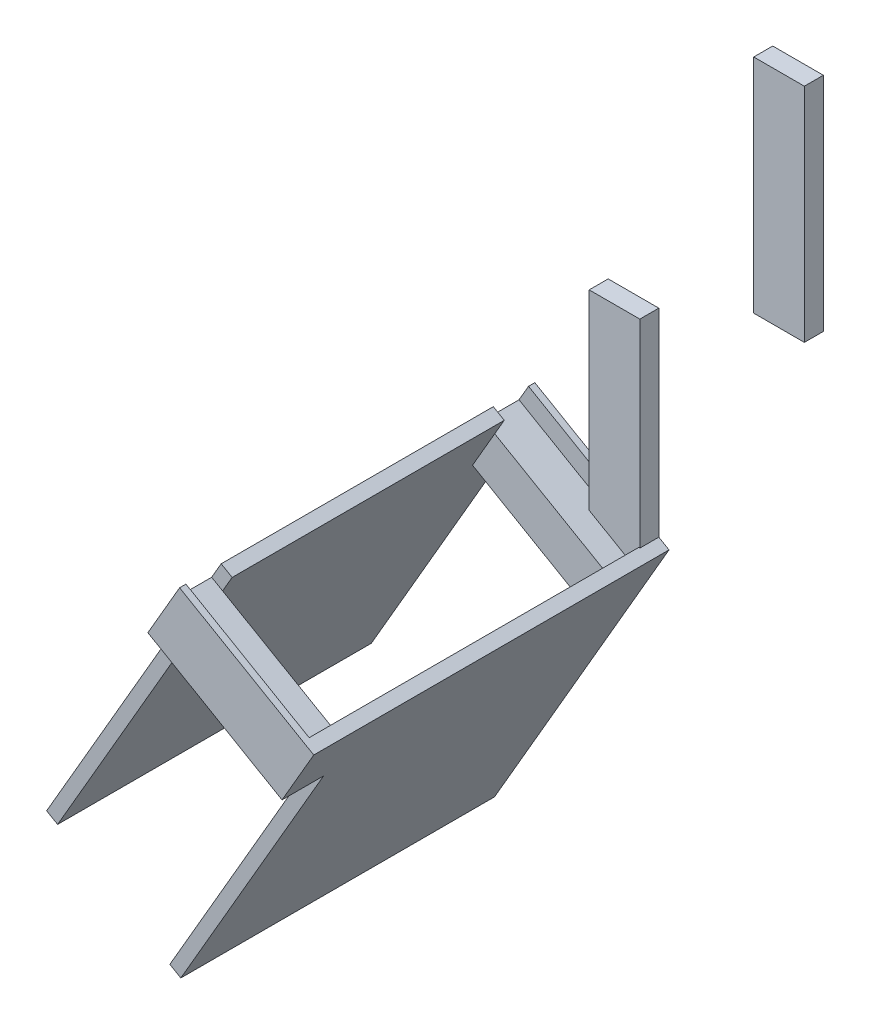
SolidWorks part; units mm, degrees
ref_plane "Front Plane" through (0, 0, 0) normal (0, 0, 1) x (1, 0, 0)
ref_plane "Top Plane" through (0, 0, 0) normal (0, 1, 0) x (1, 0, 0)
ref_plane "Right Plane" through (0, 0, 0) normal (1, 0, 0) x (0, 0, -1)
sketch "Sketch1" plane through (0, 0, 0) normal (-0.5014, -0.8652, 0) x (-0.8652, 0.5014, 0)
  line L0 (-12.25, -28.0668) -> (12.25, 28.0668) construction
  line L1 (10.25, 21.5) -> (-10.25, 21.5)
  line L2 (10.25, 21.5) -> (10.25, -21.5)
  line L3 (10.25, -21.5) -> (-10.25, -21.5)
  line L4 (-10.25, 21.5) -> (-10.25, -21.5)
  line L5 (-12.25, 28.0668) -> (12.25, 28.0668)
  line L6 (-12.25, 28.0668) -> (-12.25, -28.0668)
  line L7 (-12.25, -28.0668) -> (12.25, -28.0668)
  line L8 (12.25, 28.0668) -> (12.25, -28.0668)
  line L9 (-10.25, -21.5) -> (10.25, 21.5) construction
  line L10 (-10.25, 0) -> (-12.25, 0) construction
  line L11 (-10.25, 21.5) -> (10.25, -21.5) construction
  line L12 (10.25, 0) -> (12.25, 0) construction
  line L13 (0, 21.0668) -> (0, 28.0668) construction
  dimension "D1" = 20.5
  dimension "D2" = 43
  dimension "D3" = 2
  dimension "D4" = 7
extrude "Boss-Extrude1" add sketch "Sketch1" along normal blind 10 contours L6 L5 L8 L7
sketch "Sketch15" plane through (0, 0, 0) normal (0.5014, 0.8652, 0) x (0, 0, 1)
  line L0 (-21.5, -10.25) -> (-28.0668, -10.25) construction
  line L1 (-28.0668, -12.25) -> (-28.0668, 12.25) construction
  line L2 (21.5, -10.25) -> (28.0668, -10.25) construction
  line L3 (28.0668, 12.25) -> (28.0668, -12.25) construction
  line L4 (24.7834, -10.25) -> (24.7834, 12.25) construction
  line L5 (-28.0668, 12.25) -> (28.0668, 12.25) construction
  line L6 (-24.7834, -10.25) -> (-24.7834, 12.25) construction
sketch "Sketch5" plane through (0, 0, -28.0668) normal (0, 0, -1) x (-1, 0, 0)
  line L0 (-14.9316, -8.6523) -> (5.0137, -8.6523) construction
  line L4 (15.6128, -2.5105) -> (-5.5854, -14.7941) construction
  line L6 (8.8686, 5.139) -> (-10.5991, -6.1418) construction
sketch "Sketch16" plane through (-5.0137, -8.6523, 0) normal (-0.5014, -0.8652, 0) x (0, 0, -1)
  line L1 (-21.5, 10.25) -> (28.0668, 10.25)
  line L2 (-21.5, 10.25) -> (-21.5, 12.25)
  line L3 (-21.5, 12.25) -> (28.0668, 12.25)
  line L4 (28.0668, 10.25) -> (28.0668, 12.25)
  line L5 (28.0668, -12.25) -> (-21.5, -12.25)
  line L6 (28.0668, -12.25) -> (28.0668, -10.25)
  line L7 (28.0668, -10.25) -> (-21.5, -10.25)
  line L8 (-21.5, -12.25) -> (-21.5, -10.25)
extrude "Boss-Extrude4" add sketch "Sketch16" along normal blind 45
sketch "Sketch17" plane through (0, 0, 0) normal (0.5014, 0.8652, 0) x (0, 0, 1)
  line L0 (-28.0668, 8.6287) -> (-27.0668, -485.3229) construction
  line L1 (-21.5, 10.25) -> (-27.0668, 10.25)
  line L2 (-21.5, 10.25) -> (-21.5, -980.8958)
  line L3 (-21.5, -980.8958) -> (-27.0668, -980.8958)
  line L4 (-27.0668, 10.25) -> (-27.0668, -980.8958)
  line L5 (27.0668, -980.8958) -> (21.5, -980.8958)
  line L6 (27.0668, -980.8958) -> (27.0668, 10.25)
  line L7 (27.0668, 10.25) -> (21.5, 10.25)
  line L8 (21.5, -980.8958) -> (21.5, 10.25)
  line L9 (-28.0668, 17.2574) -> (-28.0668, 0) construction
  dimension "D1" = 1
extrude "Cut-Extrude1" cut sketch "Sketch17" against normal blind 3
sketch "Sketch18" plane through (0, 0, -28.0668) normal (0, 0, -1) x (-1, 0, 0)
  line L0 (16.9763, -53.7296) -> (-10.5991, -6.1418) construction
  line L1 (-34.9863, 35.9441) -> (-26.9863, 35.9441)
  line L2 (-34.9863, 35.9441) -> (-34.9863, 71.0043)
  line L3 (-34.9863, 71.0043) -> (-26.9863, 71.0043)
  line L4 (-26.9863, 35.9441) -> (-26.9863, 71.0043)
  line L5 (38.1745, -41.446) -> (10.5991, 6.1418) construction
  line L6 (-0.9863, 8.605) -> (5.0137, -8.6523) construction
  line L7 (-0.9863, 26.1351) -> (-8.9863, 26.1351)
  line L8 (-0.9863, 26.1351) -> (-0.9863, -8.9251)
  line L9 (-0.9863, -8.9251) -> (-8.9863, -8.9251)
  line L10 (-8.9863, 26.1351) -> (-8.9863, -8.9251)
  line L11 (-26.9863, 53.4742) -> (-8.9863, 8.605) construction
  dimension "D1" = 8
  dimension "D2" = 6
  dimension "D3" = 18
extrude "Boss-Extrude5" add sketch "Sketch18" against normal blind 3
